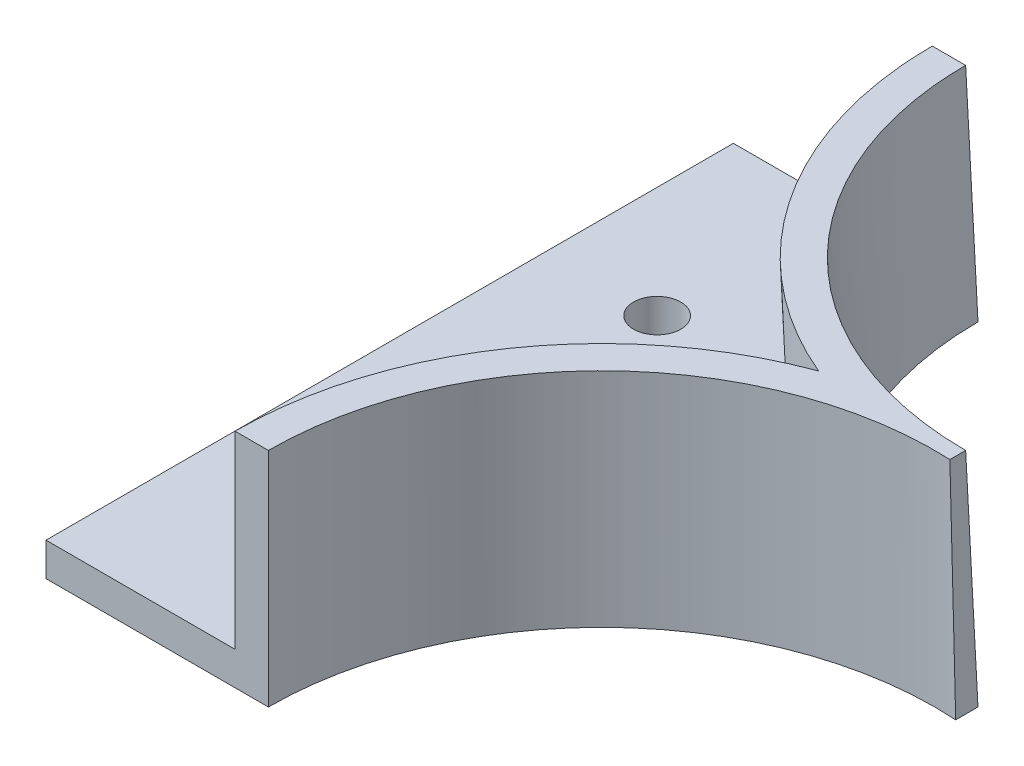
SolidWorks part; units mm, degrees
ref_plane "前基準面" through (0, 0, 0) normal (0, 0, 1) x (1, 0, 0)
ref_plane "上基準面" through (0, 0, 0) normal (0, 1, 0) x (1, 0, 0)
ref_plane "右基準面" through (0, 0, 0) normal (1, 0, 0) x (0, 0, -1)
sketch "草圖1" plane through (0, 0, 0) normal (0, 1, 0) x (1, 0, 0)
  line L0 (0, -55) -> (0, 55) construction
  line L1 (0, 30) -> (50, 30)
  line L2 (0, 30) -> (0, -30)
  line L3 (0, -30) -> (50, -30)
  line L4 (50, 30) -> (50, -30)
  line L5 (-55, 0) -> (55, 0) construction
  dimension "D1" = 50
  dimension "D2" = 60
  dimension "D3" = 30
extrude "填料-伸長1" add sketch "草圖1" along normal blind 70
draft "拔模1" type of draft neutral plane draft angle 1.591 faces to draft 2 face at (50, 35, 0) face at (25, 35, -30) neutral plane through (0, 70, 0) neutral plane normal (0, 1, 0) parameters "D1"=1.591
ref_plane "平面4" through (50, 70, -30) normal (0.0278, -0.9992, -0.0278) x (-0.9996, -0.0277, -0.0008)
sketch "草圖8" plane through (50, 70, -30) normal (0.0278, -0.9992, -0.0278) x (0.9996, 0.0277, 0.0008)
  circle A0 centre (0, 0) radius 30
extrude "除料-伸長1" cut sketch "草圖8" against normal through all and the other way through all
sketch "草圖9" plane through (0, 70, 0) normal (0, 1, 0) x (1, 0, 0)
  circle A0 centre (50, -30) radius 29.9884
extrude "除料-伸長2" cut sketch "草圖9" against normal through all
sketch "草圖10" plane through (0, 0, 0) normal (-1, 0, 0) x (0, 0, 1)
  line L0 (-30, 70) -> (-31.9443, 0) construction
  line L1 (30, 70) -> (-31.3888, 70)
  line L2 (30, 70) -> (30, 20)
  line L3 (30, 20) -> (-31.3888, 20)
  line L4 (-31.3888, 70) -> (-31.3888, 20)
  line L6 (-31.9443, 0) -> (30, 0) construction
  dimension "D1" = 20
extrude "除料-伸長3" cut sketch "草圖10" against normal through all
shell "薄殼1" thickness 3
sketch "草圖11" plane through (0, 3, 0) normal (0, 1, 0) x (1, 0, 0)
  line L0 (0, -11) -> (0, 11) construction
  line L1 (-11, 0) -> (11, 0) construction
  circle A0 centre (10, 15) radius 2.125
  circle A1 centre (10, -15) radius 2.125
  dimension "D1" = 4.25
  dimension "D2" = 10
  dimension "D3" = 15
extrude "除料-伸長4" cut sketch "草圖11" against normal through all
